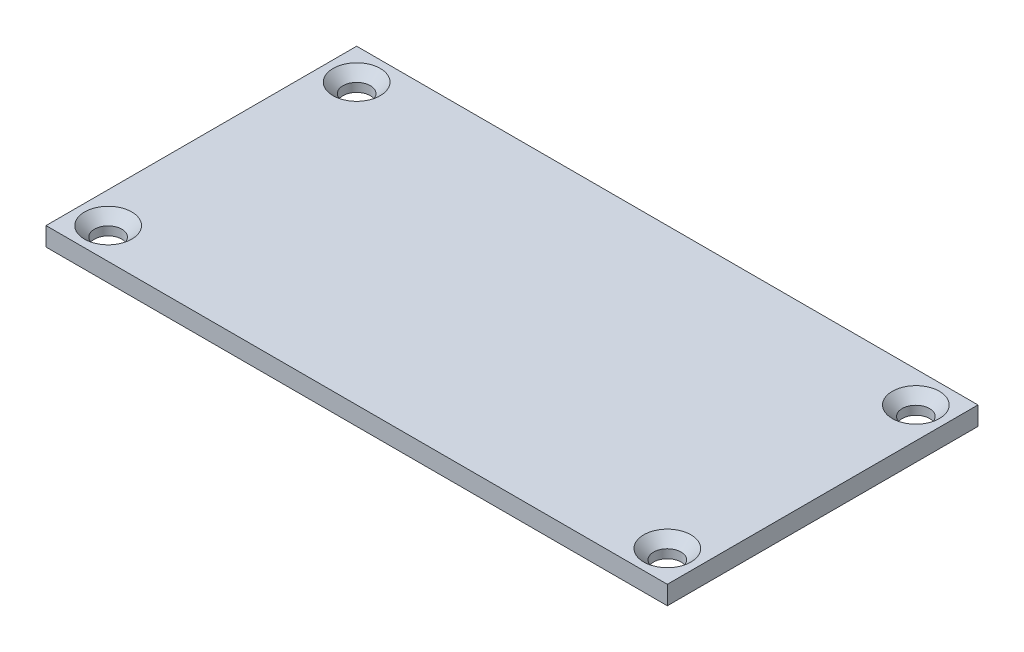
SolidWorks part; units mm, degrees
ref_plane "前视基准面" through (0, 0, 0) normal (0, 0, 1) x (1, 0, 0)
ref_plane "上视基准面" through (0, 0, 0) normal (0, 1, 0) x (1, 0, 0)
ref_plane "右视基准面" through (0, 0, 0) normal (1, 0, 0) x (0, 0, -1)
sketch "草图1" plane through (0, 0, 0) normal (0, 1, 0) x (1, 0, 0)
  line L1 (0, 0) -> (50, 0)
  line L2 (0, 0) -> (0, 25)
  line L3 (0, 25) -> (50, 25)
  line L4 (50, 0) -> (50, 25)
  dimension "D1" = 50
  dimension "D2" = 25
extrude "凸台-拉伸1" add sketch "草图1" along normal blind 1.5
hole_wizard "M2 平头机械螺钉的锥形沉头孔1" positions "草图2" profile "草图3" countersink size "M2" standard "ANSI Metric" end condition through all
sketch "草图2" plane through (0, 1.5, 0) normal (0, 1, 0) x (1, 0, 0)
  line L0 (0, 25) -> (0, 0) construction
  line L2 (50, 25) -> (0, 25) construction
  point P0 (2.5, 22.5)
  dimension "D1" = 2.5
  dimension "D2" = 2.5
sketch "草图3" plane through (2.5, 1.5, -22.5) normal (1, 0, 0) x (0, 0, 1)
  line L0 (0, 0) -> (0, 1.5)
  line L1 (0, 1.5) -> (1.1, 1.5)
  line L2 (1.1, 1.5) -> (1.1, 0.8)
  line L3 (1.1, 0.8) -> (1.9, 0)
  line L5 (1.9, 0) -> (0, 0)
  line L6 (-1.1, 0.8) -> (-1.9, 0) construction
  line L11 (0, -6.35) -> (0, 107.95) construction
  dimension "通孔孔直径" = 2.2
  dimension "通孔孔深度" = 1.5
  dimension "近端锥形沉头孔直径" = 3.8
  dimension "近端锥形沉头孔角度" = 90
pattern_linear "阵列(线性)2" count 2 spacing 45 along (1, 0, 0) count 2 spacing 20 along (0, 0, 1) of "M2 平头机械螺钉的锥形沉头孔1"
